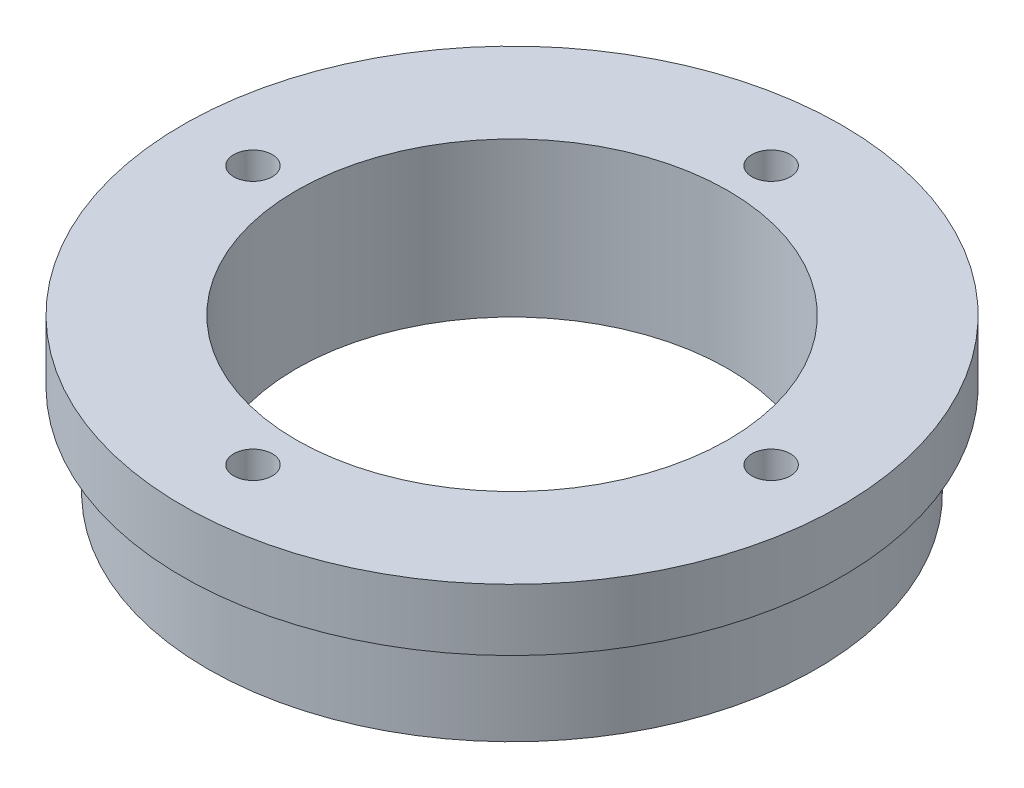
SolidWorks part; units mm, degrees
material "6061-T6 (SS)"
ref_plane "Front Plane" through (0, 0, 0) normal (0, 0, 1) x (1, 0, 0)
ref_plane "Top Plane" through (0, 0, 0) normal (0, 1, 0) x (1, 0, 0)
ref_plane "Right Plane" through (0, 0, 0) normal (1, 0, 0) x (0, 0, -1)
sketch "Sketch1" plane through (0, 0, 0) normal (0, 0, 1) x (1, 0, 0)
  line L0 (67.8561, 0) -> (44.45, 0)
  line L1 (67.8561, 0) -> (67.8561, -12.7)
  line L2 (67.8561, -12.7) -> (62.6618, -12.7)
  line L3 (62.6618, -12.7) -> (62.6618, -31.75)
  line L4 (44.45, 0) -> (44.45, -31.75)
  line L5 (0, -31.75) -> (0, 0) construction
  line L6 (44.45, -31.75) -> (62.6618, -31.75)
  dimension "D1" = 67.8561
  dimension "D2" = 62.6618
  dimension "D3" = 31.75
  dimension "D4" = 19.05
  dimension "D5" = 44.45
revolve "Revolve1" add sketch "Sketch1" angle 360 about L5
sketch "Sketch2" plane through (0, 0, 0) normal (0, 1, 0) x (1, 0, 0)
  line L0 (0, 0) -> (0, 53.34) construction
  dimension "D1" = 53.34
hole_wizard "3/8-16 Tapped Hole1" positions "3DSketch1" profile "Sketch3" tap size "3/8-16" standard "Ansi Inch"
sketch3d "3DSketch1"
  point P0 (0, 0, -53.34)
sketch "Sketch3" plane through (0, 0, -53.34) normal (1, 0, 0) x (0, 0, 1)
  line L0 (0, 0) -> (0, 29.3849)
  line L1 (0, 29.3849) -> (3.9687, 27.0002)
  line L2 (3.9687, 27.0002) -> (3.9687, 0)
  line L5 (3.9687, 0) -> (0, 0)
  line L10 (0, 29.3849) -> (-3.9688, 27.0002) construction
  line L11 (0, -6.35) -> (0, 107.95) construction
  dimension "Tap Drill Dia." = 7.9375
  dimension "Tap Drill Depth" = 27.0002
  dimension "Drill Angle" = 118
cosmetic thread "Hole Thread1" parameters "D1"=19.05, "D2"=9.525
pattern_circular "CirPattern1" count 4 over 360 about axis through (0, 0, 0) along (0, 1, 0) of "3/8-16 Tapped Hole1"
